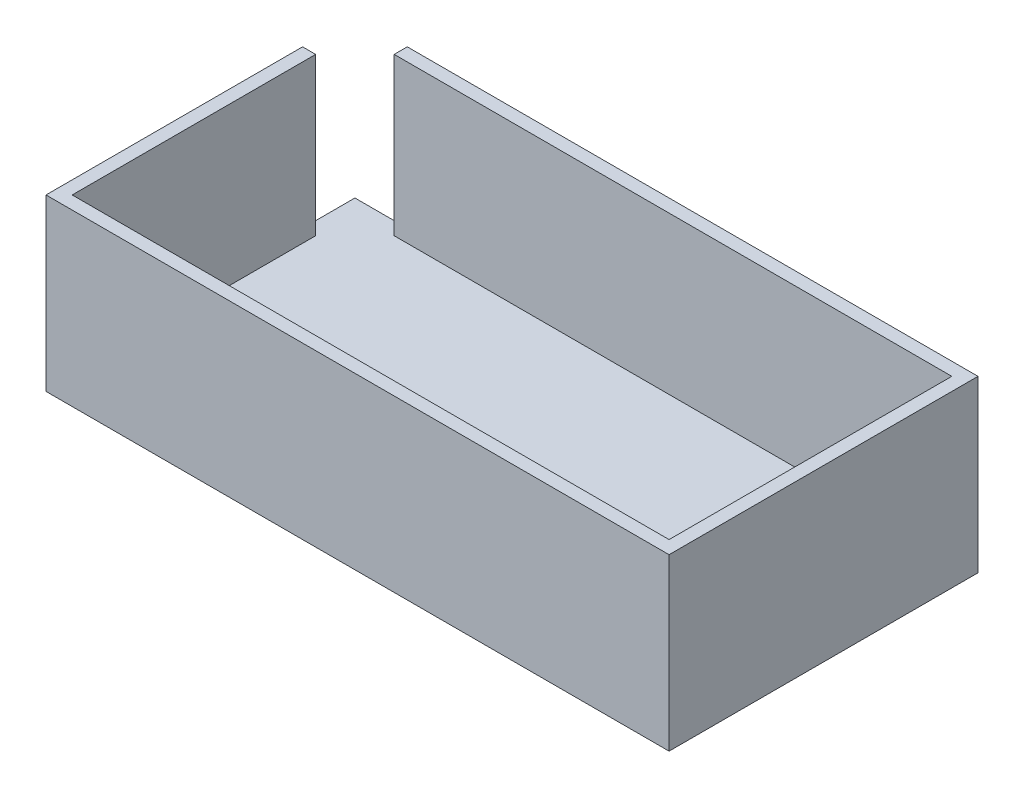
SolidWorks part; units mm, degrees
ref_plane "Front Plane" through (0, 0, 0) normal (0, 0, 1) x (1, 0, 0)
ref_plane "Top Plane" through (0, 0, 0) normal (0, 1, 0) x (1, 0, 0)
ref_plane "Right Plane" through (0, 0, 0) normal (1, 0, 0) x (0, 0, -1)
sketch "Sketch1" plane through (0, 0, 0) normal (0, 1, 0) x (1, 0, 0)
  line L0 (-1.5875, 35.8775) -> (73.9775, 35.8775)
  line L1 (0, 0) -> (72.39, 0)
  line L2 (0, 0) -> (0, 34.29)
  line L3 (0, 34.29) -> (72.39, 34.29)
  line L4 (72.39, 0) -> (72.39, 34.29)
  line L5 (73.9775, 35.8775) -> (73.9775, -1.5875)
  line L6 (73.9775, -1.5875) -> (-1.5875, -1.5875)
  line L7 (-1.5875, -1.5875) -> (-1.5875, 35.8775)
  dimension "D1" = 34.29
  dimension "D2" = 72.39
  dimension "D3" = 1.5875
  dimension "D4" = 1.5875
  dimension "D5" = 1.5875
  dimension "D6" = 1.5875
extrude "Boss-Extrude1" add sketch "Sketch1" along normal blind 19.05
sketch "Sketch2" plane through (0, 0, 0) normal (0, -1, 0) x (1, 0, 0)
  line L1 (-1.5875, 1.5875) -> (73.9775, 1.5875)
  line L2 (-1.5875, 1.5875) -> (-1.5875, -35.8775)
  line L3 (-1.5875, -35.8775) -> (73.9775, -35.8775)
  line L4 (73.9775, 1.5875) -> (73.9775, -35.8775)
extrude "Boss-Extrude2" add sketch "Sketch2" along normal blind 1.5875
sketch "Sketch3" plane through (0, 19.05, 0) normal (0, 1, 0) x (1, 0, 0)
  line L1 (-1.5875, 35.8775) -> (4.7625, 35.8775)
  line L2 (-1.5875, 35.8775) -> (-1.5875, 29.5275)
  line L3 (-1.5875, 29.5275) -> (4.7625, 29.5275)
  line L4 (4.7625, 35.8775) -> (4.7625, 29.5275)
  dimension "D1" = 6.35
  dimension "D2" = 6.35
extrude "Cut-Extrude1" cut sketch "Sketch3" against normal blind 19.05
